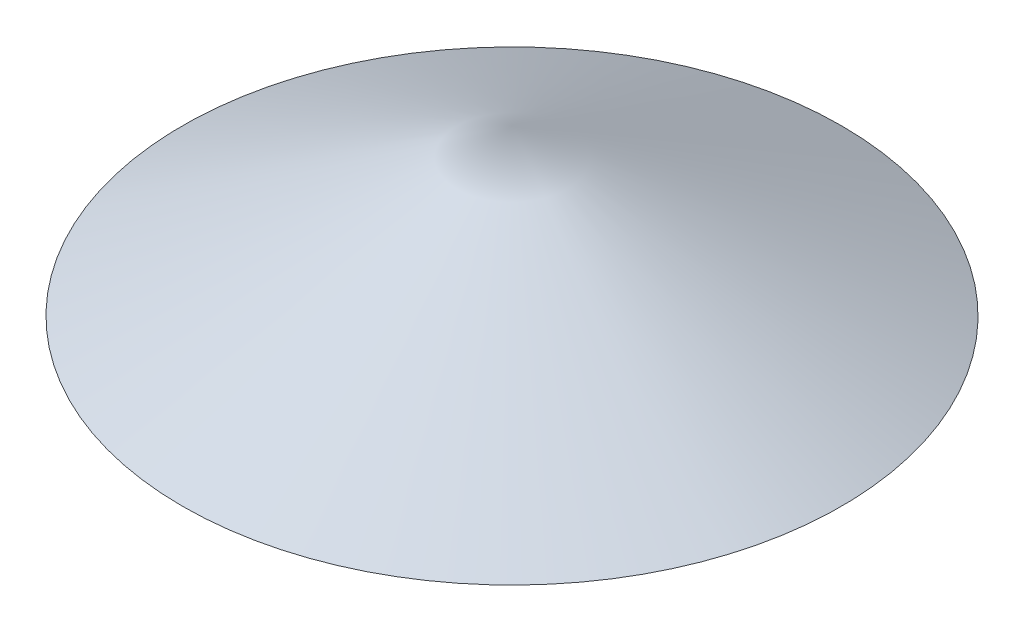
SolidWorks part; units mm, degrees
ref_plane "Front Plane" through (0, 0, 0) normal (0, 0, 1) x (1, 0, 0)
ref_plane "Top Plane" through (0, 0, 0) normal (0, 1, 0) x (1, 0, 0)
ref_plane "Right Plane" through (0, 0, 0) normal (1, 0, 0) x (0, 0, -1)
sketch "Sketch1" plane through (0, 0, 0) normal (0, 0, 1) x (1, 0, 0)
  line L0 (0, 0) -> (30, 0)
  line L1 (30, 0) -> (0, 15)
  line L2 (0, 15) -> (0, 0)
  dimension "D1" = 15
  dimension "D2" = 30
revolve "Revolve1" add sketch "Sketch1" angle 360 about L2
